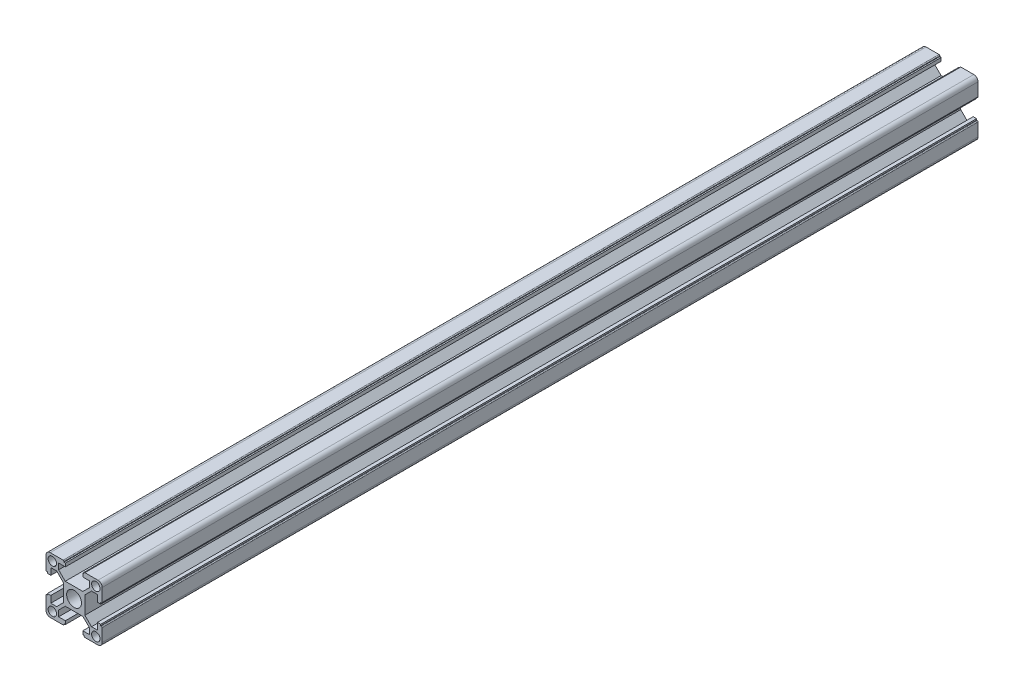
SolidWorks part; units mm, degrees
ref_plane "前视基准面" through (0, 0, 0) normal (0, 0, 1) x (1, 0, 0)
ref_plane "上视基准面" through (0, 0, 0) normal (0, 1, 0) x (1, 0, 0)
ref_plane "右视基准面" through (0, 0, 0) normal (1, 0, 0) x (0, 0, -1)
sketch "草图1" plane through (0, 0, 0) normal (0, 0, 1) x (1, 0, 0)
  line L0 (-7.75, 0) -> (0, 0) construction
  line L1 (7.75, -7.75) -> (-7.75, -7.75) construction
  line L2 (7.75, -7.75) -> (7.75, 7.75) construction
  line L3 (7.75, 7.75) -> (-7.75, 7.75) construction
  line L4 (-7.75, -7.75) -> (-7.75, 7.75) construction
  line L5 (7.75, -7.75) -> (-7.75, 7.75) construction
  line L6 (7.75, 7.75) -> (-7.75, -7.75) construction
  line L7 (0, 0) -> (0, 7.75) construction
  line L8 (3.1429, 3.85) -> (-3.1429, 3.85)
  line L9 (-3.1429, 3.85) -> (-5.5, 6.2071)
  line L10 (-5.5, 6.2071) -> (-5.5, 8.3)
  line L11 (-5.5, 8.3) -> (-3.1, 8.3)
  line L12 (-3.1, 8.3) -> (-3.1, 9.5)
  line L13 (-3.1, 9.5) -> (-3.6, 9.5)
  line L14 (-3.6, 9.5) -> (-3.6, 9.7)
  line L15 (-3.9, 10) -> (-8.5, 10)
  line L16 (-3.85, -3.1429) -> (-3.85, 3.1429)
  line L17 (-3.85, 3.1429) -> (-6.2071, 5.5)
  line L18 (-6.2071, 5.5) -> (-8.3, 5.5)
  line L19 (-8.3, 5.5) -> (-8.3, 3.1)
  line L20 (-9.5, 3.1) -> (-9.5, 3.6)
  line L21 (-8.3, 3.1) -> (-9.5, 3.1)
  line L22 (-9.5, 3.6) -> (-9.7, 3.6)
  line L23 (-10, 3.9) -> (-10, 8.5)
  line L24 (5.5, 8.3) -> (3.1, 8.3)
  line L25 (3.6, 9.5) -> (3.6, 9.7)
  line L26 (3.1, 9.5) -> (3.6, 9.5)
  line L27 (3.1, 8.3) -> (3.1, 9.5)
  line L28 (5.5, 6.2071) -> (5.5, 8.3)
  line L29 (3.1429, 3.85) -> (5.5, 6.2071)
  line L30 (3.85, -3.1429) -> (3.85, 3.1429)
  line L31 (3.85, 3.1429) -> (6.2071, 5.5)
  line L32 (9.5, 3.6) -> (9.7, 3.6)
  line L33 (8.3, 3.1) -> (9.5, 3.1)
  line L34 (9.5, 3.1) -> (9.5, 3.6)
  line L35 (8.3, 5.5) -> (8.3, 3.1)
  line L36 (6.2071, 5.5) -> (8.3, 5.5)
  line L37 (10, 3.9) -> (10, 8.5)
  line L38 (3.9, 10) -> (8.5, 10)
  line L39 (-9.5, -3.6) -> (-9.7, -3.6)
  line L40 (-8.3, -3.1) -> (-9.5, -3.1)
  line L41 (-9.5, -3.1) -> (-9.5, -3.6)
  line L42 (-8.3, -5.5) -> (-8.3, -3.1)
  line L43 (-6.2071, -5.5) -> (-8.3, -5.5)
  line L44 (-3.85, -3.1429) -> (-6.2071, -5.5)
  line L45 (-3.1429, -3.85) -> (-5.5, -6.2071)
  line L46 (-5.5, -6.2071) -> (-5.5, -8.3)
  line L47 (-3.6, -9.5) -> (-3.6, -9.7)
  line L48 (-3.1, -9.5) -> (-3.6, -9.5)
  line L49 (-3.1, -8.3) -> (-3.1, -9.5)
  line L50 (-5.5, -8.3) -> (-3.1, -8.3)
  line L51 (5.5, -6.2071) -> (5.5, -8.3)
  line L52 (3.1, -8.3) -> (3.1, -9.5)
  line L53 (3.1, -9.5) -> (3.6, -9.5)
  line L54 (3.6, -9.5) -> (3.6, -9.7)
  line L55 (5.5, -8.3) -> (3.1, -8.3)
  line L56 (3.1429, -3.85) -> (5.5, -6.2071)
  line L57 (3.1429, -3.85) -> (-3.1429, -3.85)
  line L58 (3.85, -3.1429) -> (6.2071, -5.5)
  line L59 (6.2071, -5.5) -> (8.3, -5.5)
  line L60 (8.3, -5.5) -> (8.3, -3.1)
  line L61 (9.5, -3.1) -> (9.5, -3.6)
  line L62 (8.3, -3.1) -> (9.5, -3.1)
  line L63 (9.5, -3.6) -> (9.7, -3.6)
  line L64 (3.9, -10) -> (8.5, -10)
  line L65 (10, -3.9) -> (10, -8.5)
  line L66 (-10, -3.9) -> (-10, -8.5)
  line L67 (-3.9, -10) -> (-8.5, -10)
  circle A0 centre (0, 0) radius 2.65
  circle A1 centre (-7.75, 7.75) radius 1.5
  circle A2 centre (7.75, 7.75) radius 1.5
  circle A3 centre (7.75, -7.75) radius 1.5
  circle A4 centre (-7.75, -7.75) radius 1.5
  arc A5 (-10, -8.5) -> (-8.5, -10) centre (-8.5, -8.5) ccw
  arc A6 (8.5, -10) -> (10, -8.5) centre (8.5, -8.5) ccw
  arc A7 (10, 8.5) -> (8.5, 10) centre (8.5, 8.5) ccw
  arc A8 (-8.5, 10) -> (-10, 8.5) centre (-8.5, 8.5) ccw
  arc A9 (3.6, -9.7) -> (3.9, -10) centre (3.9, -9.7) ccw
  arc A10 (-3.6, -9.7) -> (-3.9, -10) centre (-3.9, -9.7) cw
  arc A11 (-9.7, -3.6) -> (-10, -3.9) centre (-9.7, -3.9) ccw
  arc A12 (9.7, -3.6) -> (10, -3.9) centre (9.7, -3.9) cw
  arc A13 (9.7, 3.6) -> (10, 3.9) centre (9.7, 3.9) ccw
  arc A14 (-9.7, 3.6) -> (-10, 3.9) centre (-9.7, 3.9) cw
  arc A15 (3.6, 9.7) -> (3.9, 10) centre (3.9, 9.7) cw
  arc A16 (-3.6, 9.7) -> (-3.9, 10) centre (-3.9, 9.7) ccw
  point P46 (0, 3.85)
  point P56 (-3.85, 0)
  point P78 (3.85, 0)
  point P87 (-10, -10)
  point P90 (10, -10)
  point P93 (10, 10)
  point P96 (-10, 10)
  point P99 (3.6, -10)
  point P102 (-3.6, -10)
  point P105 (-10, -3.6)
  point P108 (10, -3.6)
  point P111 (10, 3.6)
  point P114 (-10, 3.6)
  point P117 (3.6, 10)
  point P120 (-3.6, 10)
  dimension "D1" = 5.3
  dimension "D2" = 3
  dimension "D11" = 1.5
  dimension "D12" = 2.25
  dimension "D13" = 0.3
  dimension "D3" = 7.7
  dimension "D4" = 6.2
  dimension "D5" = 1.7
  dimension "D6" = 1.2
  dimension "D7" = 20
  dimension "D8" = 7.2
  dimension "D9" = 11
  dimension "D10" = 1
extrude "凸台-拉伸1" add sketch "草图1" along normal mid plane 312
